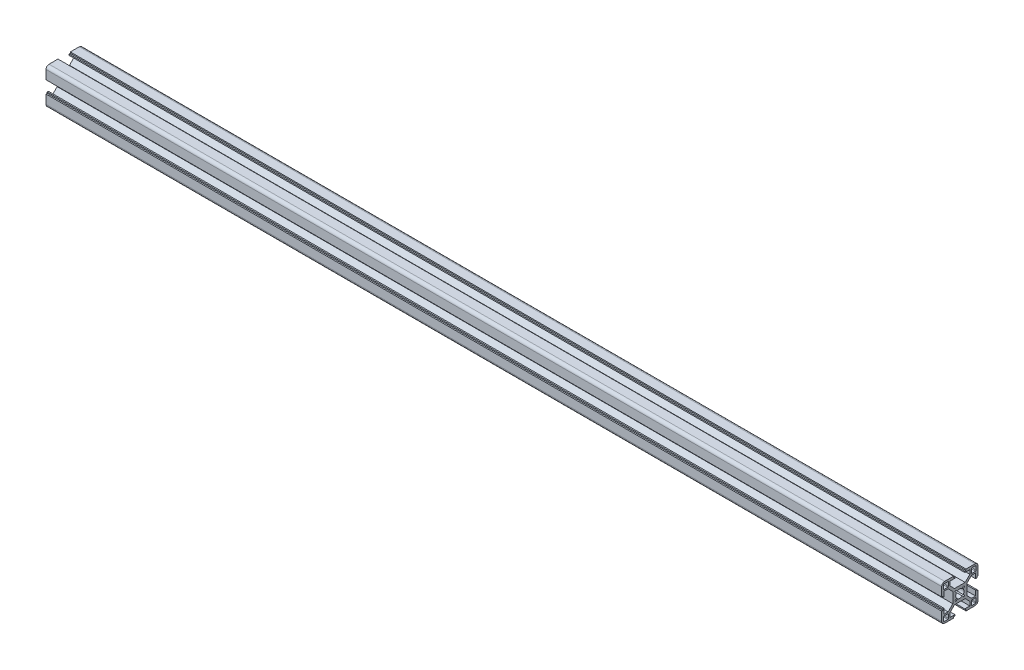
SolidWorks part; units mm, degrees
ref_plane "前视基准面" through (0, 0, 0) normal (0, 0, 1) x (1, 0, 0)
ref_plane "上视基准面" through (0, 0, 0) normal (0, 1, 0) x (1, 0, 0)
ref_plane "右视基准面" through (0, 0, 0) normal (1, 0, 0) x (0, 0, -1)
other "Configuration Table"
sketch "草图1" plane through (0, 0, 0) normal (1, 0, 0) x (0, 0, -1)
  line L0 (-5.1496, -13.7047) -> (-4.1496, -13.7047)
  line L1 (-4.1496, -13.7047) -> (-4.1496, -12.7047)
  line L2 (-4.1496, -12.7047) -> (-8.2996, -12.7047)
  line L3 (-8.2996, -12.7047) -> (-8.2996, -9.3689)
  line L4 (-8.2996, -9.3689) -> (-4.4354, -5.5047)
  line L5 (-4.4354, -5.5047) -> (4.3362, -5.5047)
  line L6 (4.3362, -5.5047) -> (8.2004, -9.3689)
  line L7 (8.2004, -9.3689) -> (8.2004, -12.7047)
  line L8 (8.2004, -12.7047) -> (4.0504, -12.7047)
  line L9 (4.0504, -12.7047) -> (4.0504, -13.7047)
  line L10 (4.0504, -13.7047) -> (5.0504, -13.7047)
  line L11 (5.0504, -13.7047) -> (5.0504, -14.7047)
  line L12 (5.0504, -14.7047) -> (12.4504, -14.7047)
  line L13 (14.9504, -12.2047) -> (14.9504, -4.8047)
  line L14 (14.9504, -4.8047) -> (13.9504, -4.8047)
  line L15 (13.9504, -4.8047) -> (13.9504, -3.8047)
  line L16 (13.9504, -3.8047) -> (12.9504, -3.8047)
  line L17 (12.9504, -3.8047) -> (12.9504, -7.9547)
  line L18 (12.9504, -7.9547) -> (9.6146, -7.9547)
  line L19 (9.6146, -7.9547) -> (5.7504, -4.0905)
  line L20 (5.7504, -4.0905) -> (5.7504, 4.6811)
  line L21 (5.7504, 4.6811) -> (9.6146, 8.5453)
  line L22 (9.6146, 8.5453) -> (12.9504, 8.5453)
  line L23 (12.9504, 8.5453) -> (12.9504, 4.3953)
  line L24 (12.9504, 4.3953) -> (13.9504, 4.3953)
  line L25 (13.9504, 4.3953) -> (13.9504, 5.3953)
  line L26 (13.9504, 5.3953) -> (14.9504, 5.3953)
  line L27 (14.9504, 5.3953) -> (14.9504, 12.7953)
  line L28 (12.4504, 15.2953) -> (5.0504, 15.2953)
  line L29 (5.0504, 15.2953) -> (5.0504, 14.2953)
  line L30 (5.0504, 14.2953) -> (4.0504, 14.2953)
  line L31 (4.0504, 14.2953) -> (4.0504, 13.2953)
  line L32 (4.0504, 13.2953) -> (8.2004, 13.2953)
  line L33 (8.2004, 13.2953) -> (8.2004, 9.9595)
  line L34 (8.2004, 9.9595) -> (4.3362, 6.0953)
  line L35 (4.3362, 6.0953) -> (-4.4354, 6.0953)
  line L36 (-4.4354, 6.0953) -> (-8.2996, 9.9595)
  line L37 (-8.2996, 9.9595) -> (-8.2996, 13.2953)
  line L38 (-8.2996, 13.2953) -> (-4.1496, 13.2953)
  line L39 (-4.1496, 13.2953) -> (-4.1496, 14.2953)
  line L40 (-4.1496, 14.2953) -> (-5.1496, 14.2953)
  line L41 (-5.1496, 14.2953) -> (-5.1496, 15.2953)
  line L42 (-5.1496, 15.2953) -> (-12.5496, 15.2953)
  line L43 (-15.0496, 12.7953) -> (-15.0496, 5.3953)
  line L44 (-15.0496, 5.3953) -> (-14.0496, 5.3953)
  line L45 (-14.0496, 5.3953) -> (-14.0496, 4.3953)
  line L46 (-14.0496, 4.3953) -> (-13.0496, 4.3953)
  line L47 (-13.0496, 4.3953) -> (-13.0496, 8.5453)
  line L48 (-13.0496, 8.5453) -> (-9.7138, 8.5453)
  line L49 (-9.7138, 8.5453) -> (-5.8496, 4.6811)
  line L50 (-5.8496, 4.6811) -> (-5.8496, -4.0905)
  line L51 (-5.8496, -4.0905) -> (-9.7138, -7.9547)
  line L52 (-9.7138, -7.9547) -> (-13.0496, -7.9547)
  line L53 (-13.0496, -7.9547) -> (-13.0496, -3.8047)
  line L54 (-13.0496, -3.8047) -> (-14.0496, -3.8047)
  line L55 (-14.0496, -3.8047) -> (-14.0496, -4.8047)
  line L56 (-14.0496, -4.8047) -> (-15.0496, -4.8047)
  line L57 (-15.0496, -4.8047) -> (-15.0496, -12.2047)
  line L58 (-12.5496, -14.7047) -> (-5.1496, -14.7047)
  line L59 (-5.1496, -14.7047) -> (-5.1496, -13.7047)
  line L60 (-10.0496, 9.7953) -> (-13.0496, 9.7953)
  line L61 (-13.5496, 10.2953) -> (-13.5496, 13.2953)
  line L62 (-13.0496, 13.7953) -> (-10.0496, 13.7953)
  line L63 (-9.5496, 13.2953) -> (-9.5496, 10.2953)
  line L64 (-10.0496, -13.2047) -> (-13.0496, -13.2047)
  line L65 (-13.5496, -12.7047) -> (-13.5496, -9.7047)
  line L66 (-13.0496, -9.2047) -> (-10.0496, -9.2047)
  line L67 (-9.5496, -9.7047) -> (-9.5496, -12.7047)
  line L68 (12.9504, 9.7953) -> (9.9504, 9.7953)
  line L69 (9.4504, 10.2953) -> (9.4504, 13.2953)
  line L70 (9.9504, 13.7953) -> (12.9504, 13.7953)
  line L71 (13.4504, 13.2953) -> (13.4504, 10.2953)
  line L72 (13.4504, -9.7047) -> (13.4504, -12.7047)
  line L73 (12.9504, -13.2047) -> (9.9504, -13.2047)
  line L74 (9.4504, -12.7047) -> (9.4504, -9.7047)
  line L75 (9.9504, -9.2047) -> (12.9504, -9.2047)
  line L76 (-4.08, 3.6186) -> (-3.3729, 4.3257)
  line L77 (-3.3729, 4.3257) -> (-2.074, 3.0269)
  line L78 (1.9749, 3.0269) -> (3.2737, 4.3257)
  line L79 (3.2737, 4.3257) -> (3.9808, 3.6186)
  line L80 (3.9808, 3.6186) -> (2.682, 2.3198)
  line L81 (2.682, -1.7291) -> (3.9808, -3.028)
  line L82 (3.9808, -3.028) -> (3.2737, -3.7351)
  line L83 (3.2737, -3.7351) -> (1.9749, -2.4362)
  line L84 (-2.074, -2.4362) -> (-3.3729, -3.7351)
  line L85 (-3.3729, -3.7351) -> (-4.08, -3.028)
  line L86 (-4.08, -3.028) -> (-2.7811, -1.7291)
  line L87 (-2.7811, 2.3198) -> (-4.08, 3.6186)
  arc A0 (12.4504, -14.7047) -> (14.9504, -12.2047) centre (12.4504, -12.2047) ccw
  arc A1 (14.9504, 12.7953) -> (12.4504, 15.2953) centre (12.4504, 12.7953) ccw
  arc A2 (-12.5496, 15.2953) -> (-15.0496, 12.7953) centre (-12.5496, 12.7953) ccw
  arc A3 (-15.0496, -12.2047) -> (-12.5496, -14.7047) centre (-12.5496, -12.2047) ccw
  arc A4 (-9.5496, 10.2953) -> (-10.0496, 9.7953) centre (-10.0496, 10.2953) cw
  arc A5 (-13.0496, 9.7953) -> (-13.5496, 10.2953) centre (-13.0496, 10.2953) cw
  arc A6 (-13.5496, 13.2953) -> (-13.0496, 13.7953) centre (-13.0496, 13.2953) cw
  arc A7 (-10.0496, 13.7953) -> (-9.5496, 13.2953) centre (-10.0496, 13.2953) cw
  arc A8 (-9.5496, -12.7047) -> (-10.0496, -13.2047) centre (-10.0496, -12.7047) cw
  arc A9 (-13.0496, -13.2047) -> (-13.5496, -12.7047) centre (-13.0496, -12.7047) cw
  arc A10 (-13.5496, -9.7047) -> (-13.0496, -9.2047) centre (-13.0496, -9.7047) cw
  arc A11 (-10.0496, -9.2047) -> (-9.5496, -9.7047) centre (-10.0496, -9.7047) cw
  arc A12 (13.4504, 10.2953) -> (12.9504, 9.7953) centre (12.9504, 10.2953) cw
  arc A13 (9.9504, 9.7953) -> (9.4504, 10.2953) centre (9.9504, 10.2953) cw
  arc A14 (9.4504, 13.2953) -> (9.9504, 13.7953) centre (9.9504, 13.2953) cw
  arc A15 (12.9504, 13.7953) -> (13.4504, 13.2953) centre (12.9504, 13.2953) cw
  arc A16 (12.9504, -9.2047) -> (13.4504, -9.7047) centre (12.9504, -9.7047) cw
  arc A17 (13.4504, -12.7047) -> (12.9504, -13.2047) centre (12.9504, -12.7047) cw
  arc A18 (9.9504, -13.2047) -> (9.4504, -12.7047) centre (9.9504, -12.7047) cw
  arc A19 (9.4504, -9.7047) -> (9.9504, -9.2047) centre (9.9504, -9.7047) cw
  arc A20 (-2.074, 3.0269) -> (1.9749, 3.0269) centre (-0.0496, 0.2953) cw
  arc A21 (2.682, 2.3198) -> (2.682, -1.7291) centre (-0.0496, 0.2953) cw
  arc A22 (1.9749, -2.4362) -> (-2.074, -2.4362) centre (-0.0496, 0.2953) cw
  arc A23 (-2.7811, -1.7291) -> (-2.7811, 2.3198) centre (-0.0496, 0.2953) cw
extrude "凸台-拉伸1" add sketch "草图1" against normal blind 50
sketch "草图2" plane through (0, 0, 0) normal (1, 0, 0) x (0, 0, -1)
  line L4 (-13.0496, 9.7953) -> (-10.0496, 9.7953)
  line L5 (-13.5496, 13.2953) -> (-13.5496, 10.2953)
  line L6 (-10.0496, 13.7953) -> (-13.0496, 13.7953)
  line L7 (-9.5496, 10.2953) -> (-9.5496, 13.2953)
  line L8 (-13.0496, 9.7953) -> (-10.0496, 9.7953)
  line L9 (-13.5496, 13.2953) -> (-13.5496, 10.2953)
  line L10 (-10.0496, 13.7953) -> (-13.0496, 13.7953)
  line L11 (-9.5496, 10.2953) -> (-9.5496, 13.2953)
  line L12 (-13.0496, -13.2047) -> (-10.0496, -13.2047)
  line L13 (-13.5496, -9.7047) -> (-13.5496, -12.7047)
  line L14 (-10.0496, -9.2047) -> (-13.0496, -9.2047)
  line L15 (-9.5496, -12.7047) -> (-9.5496, -9.7047)
  line L16 (-13.0496, -13.2047) -> (-10.0496, -13.2047)
  line L17 (-13.5496, -9.7047) -> (-13.5496, -12.7047)
  line L18 (-10.0496, -9.2047) -> (-13.0496, -9.2047)
  line L19 (-9.5496, -12.7047) -> (-9.5496, -9.7047)
  line L20 (9.4504, 13.2953) -> (9.4504, 10.2953)
  line L21 (12.9504, 13.7953) -> (9.9504, 13.7953)
  line L22 (13.4504, 10.2953) -> (13.4504, 13.2953)
  line L23 (9.9504, 9.7953) -> (12.9504, 9.7953)
  line L24 (9.4504, 13.2953) -> (9.4504, 10.2953)
  line L25 (12.9504, 13.7953) -> (9.9504, 13.7953)
  line L26 (13.4504, 10.2953) -> (13.4504, 13.2953)
  line L27 (9.9504, 9.7953) -> (12.9504, 9.7953)
  line L28 (9.4504, -9.7047) -> (9.4504, -12.7047)
  line L29 (12.9504, -9.2047) -> (9.9504, -9.2047)
  line L30 (13.4504, -12.7047) -> (13.4504, -9.7047)
  line L31 (9.9504, -13.2047) -> (12.9504, -13.2047)
  line L32 (9.4504, -9.7047) -> (9.4504, -12.7047)
  line L33 (12.9504, -9.2047) -> (9.9504, -9.2047)
  line L34 (13.4504, -12.7047) -> (13.4504, -9.7047)
  line L35 (9.9504, -13.2047) -> (12.9504, -13.2047)
  line L44 (-3.3729, -3.7351) -> (-2.074, -2.4362)
  line L45 (-4.08, -3.028) -> (-3.3729, -3.7351)
  line L46 (-2.7811, -1.7291) -> (-4.08, -3.028)
  line L47 (-4.08, 3.6186) -> (-2.7811, 2.3198)
  line L48 (-3.3729, 4.3257) -> (-4.08, 3.6186)
  line L49 (-2.074, 3.0269) -> (-3.3729, 4.3257)
  line L50 (3.2737, 4.3257) -> (1.9749, 3.0269)
  line L51 (3.9808, 3.6186) -> (3.2737, 4.3257)
  line L52 (2.682, 2.3198) -> (3.9808, 3.6186)
  line L53 (3.9808, -3.028) -> (2.682, -1.7291)
  line L54 (3.2737, -3.7351) -> (3.9808, -3.028)
  line L55 (1.9749, -2.4362) -> (3.2737, -3.7351)
  line L56 (-3.3729, -3.7351) -> (-2.074, -2.4362)
  line L57 (-4.08, -3.028) -> (-3.3729, -3.7351)
  line L58 (-2.7811, -1.7291) -> (-4.08, -3.028)
  line L59 (-4.08, 3.6186) -> (-2.7811, 2.3198)
  line L60 (-3.3729, 4.3257) -> (-4.08, 3.6186)
  line L61 (-2.074, 3.0269) -> (-3.3729, 4.3257)
  line L62 (3.2737, 4.3257) -> (1.9749, 3.0269)
  line L63 (3.9808, 3.6186) -> (3.2737, 4.3257)
  line L64 (2.682, 2.3198) -> (3.9808, 3.6186)
  line L65 (3.9808, -3.028) -> (2.682, -1.7291)
  line L66 (3.2737, -3.7351) -> (3.9808, -3.028)
  line L67 (1.9749, -2.4362) -> (3.2737, -3.7351)
  line L68 (-15.0496, -4.8047) -> (-15.0496, -12.2047)
  line L69 (-14.0496, -4.8047) -> (-15.0496, -4.8047)
  line L70 (-14.0496, -3.8047) -> (-14.0496, -4.8047)
  line L71 (-13.0496, -3.8047) -> (-14.0496, -3.8047)
  line L72 (-13.0496, -7.9547) -> (-13.0496, -3.8047)
  line L73 (-9.7138, -7.9547) -> (-13.0496, -7.9547)
  line L74 (-5.8496, -4.0905) -> (-9.7138, -7.9547)
  line L75 (-5.8496, 4.6811) -> (-5.8496, -4.0905)
  line L76 (-9.7138, 8.5453) -> (-5.8496, 4.6811)
  line L77 (-13.0496, 8.5453) -> (-9.7138, 8.5453)
  line L78 (-13.0496, 4.3953) -> (-13.0496, 8.5453)
  line L79 (-14.0496, 4.3953) -> (-13.0496, 4.3953)
  line L80 (-14.0496, 5.3953) -> (-14.0496, 4.3953)
  line L81 (-15.0496, 5.3953) -> (-14.0496, 5.3953)
  line L82 (-15.0496, 12.7953) -> (-15.0496, 5.3953)
  line L83 (-5.1496, 15.2953) -> (-12.5496, 15.2953)
  line L84 (-5.1496, 14.2953) -> (-5.1496, 15.2953)
  line L85 (-4.1496, 14.2953) -> (-5.1496, 14.2953)
  line L86 (-4.1496, 13.2953) -> (-4.1496, 14.2953)
  line L87 (-8.2996, 13.2953) -> (-4.1496, 13.2953)
  line L88 (-8.2996, 9.9595) -> (-8.2996, 13.2953)
  line L89 (-4.4354, 6.0953) -> (-8.2996, 9.9595)
  line L90 (4.3362, 6.0953) -> (-4.4354, 6.0953)
  line L91 (8.2004, 9.9595) -> (4.3362, 6.0953)
  line L92 (8.2004, 13.2953) -> (8.2004, 9.9595)
  line L93 (4.0504, 13.2953) -> (8.2004, 13.2953)
  line L94 (4.0504, 14.2953) -> (4.0504, 13.2953)
  line L95 (5.0504, 14.2953) -> (4.0504, 14.2953)
  line L96 (5.0504, 15.2953) -> (5.0504, 14.2953)
  line L97 (12.4504, 15.2953) -> (5.0504, 15.2953)
  line L98 (14.9504, 5.3953) -> (14.9504, 12.7953)
  line L99 (13.9504, 5.3953) -> (14.9504, 5.3953)
  line L100 (13.9504, 4.3953) -> (13.9504, 5.3953)
  line L101 (12.9504, 4.3953) -> (13.9504, 4.3953)
  line L102 (12.9504, 8.5453) -> (12.9504, 4.3953)
  line L103 (9.6146, 8.5453) -> (12.9504, 8.5453)
  line L104 (5.7504, 4.6811) -> (9.6146, 8.5453)
  line L105 (5.7504, -4.0905) -> (5.7504, 4.6811)
  line L106 (9.6146, -7.9547) -> (5.7504, -4.0905)
  line L107 (12.9504, -7.9547) -> (9.6146, -7.9547)
  line L108 (12.9504, -3.8047) -> (12.9504, -7.9547)
  line L109 (13.9504, -3.8047) -> (12.9504, -3.8047)
  line L110 (13.9504, -4.8047) -> (13.9504, -3.8047)
  line L111 (14.9504, -4.8047) -> (13.9504, -4.8047)
  line L112 (14.9504, -12.2047) -> (14.9504, -4.8047)
  line L113 (5.0504, -14.7047) -> (12.4504, -14.7047)
  line L114 (5.0504, -13.7047) -> (5.0504, -14.7047)
  line L115 (4.0504, -13.7047) -> (5.0504, -13.7047)
  line L116 (4.0504, -12.7047) -> (4.0504, -13.7047)
  line L117 (8.2004, -12.7047) -> (4.0504, -12.7047)
  line L118 (8.2004, -9.3689) -> (8.2004, -12.7047)
  line L119 (4.3362, -5.5047) -> (8.2004, -9.3689)
  line L120 (-4.4354, -5.5047) -> (4.3362, -5.5047)
  line L121 (-8.2996, -9.3689) -> (-4.4354, -5.5047)
  line L122 (-8.2996, -12.7047) -> (-8.2996, -9.3689)
  line L123 (-4.1496, -12.7047) -> (-8.2996, -12.7047)
  line L124 (-4.1496, -13.7047) -> (-4.1496, -12.7047)
  line L125 (-5.1496, -13.7047) -> (-4.1496, -13.7047)
  line L126 (-5.1496, -14.7047) -> (-5.1496, -13.7047)
  line L127 (-12.5496, -14.7047) -> (-5.1496, -14.7047)
  line L128 (-15.0496, -4.8047) -> (-15.0496, -12.2047)
  line L129 (-14.0496, -4.8047) -> (-15.0496, -4.8047)
  line L130 (-14.0496, -3.8047) -> (-14.0496, -4.8047)
  line L131 (-13.0496, -3.8047) -> (-14.0496, -3.8047)
  line L132 (-13.0496, -7.9547) -> (-13.0496, -3.8047)
  line L133 (-9.7138, -7.9547) -> (-13.0496, -7.9547)
  line L134 (-5.8496, -4.0905) -> (-9.7138, -7.9547)
  line L135 (-5.8496, 4.6811) -> (-5.8496, -4.0905)
  line L136 (-9.7138, 8.5453) -> (-5.8496, 4.6811)
  line L137 (-13.0496, 8.5453) -> (-9.7138, 8.5453)
  line L138 (-13.0496, 4.3953) -> (-13.0496, 8.5453)
  line L139 (-14.0496, 4.3953) -> (-13.0496, 4.3953)
  line L140 (-14.0496, 5.3953) -> (-14.0496, 4.3953)
  line L141 (-15.0496, 5.3953) -> (-14.0496, 5.3953)
  line L142 (-15.0496, 12.7953) -> (-15.0496, 5.3953)
  line L143 (-5.1496, 15.2953) -> (-12.5496, 15.2953)
  line L144 (-5.1496, 14.2953) -> (-5.1496, 15.2953)
  line L145 (-4.1496, 14.2953) -> (-5.1496, 14.2953)
  line L146 (-4.1496, 13.2953) -> (-4.1496, 14.2953)
  line L147 (-8.2996, 13.2953) -> (-4.1496, 13.2953)
  line L148 (-8.2996, 9.9595) -> (-8.2996, 13.2953)
  line L149 (-4.4354, 6.0953) -> (-8.2996, 9.9595)
  line L150 (4.3362, 6.0953) -> (-4.4354, 6.0953)
  line L151 (8.2004, 9.9595) -> (4.3362, 6.0953)
  line L152 (8.2004, 13.2953) -> (8.2004, 9.9595)
  line L153 (4.0504, 13.2953) -> (8.2004, 13.2953)
  line L154 (4.0504, 14.2953) -> (4.0504, 13.2953)
  line L155 (5.0504, 14.2953) -> (4.0504, 14.2953)
  line L156 (5.0504, 15.2953) -> (5.0504, 14.2953)
  line L157 (12.4504, 15.2953) -> (5.0504, 15.2953)
  line L158 (14.9504, 5.3953) -> (14.9504, 12.7953)
  line L159 (13.9504, 5.3953) -> (14.9504, 5.3953)
  line L160 (13.9504, 4.3953) -> (13.9504, 5.3953)
  line L161 (12.9504, 4.3953) -> (13.9504, 4.3953)
  line L162 (12.9504, 8.5453) -> (12.9504, 4.3953)
  line L163 (9.6146, 8.5453) -> (12.9504, 8.5453)
  line L164 (5.7504, 4.6811) -> (9.6146, 8.5453)
  line L165 (5.7504, -4.0905) -> (5.7504, 4.6811)
  line L166 (9.6146, -7.9547) -> (5.7504, -4.0905)
  line L167 (12.9504, -7.9547) -> (9.6146, -7.9547)
  line L168 (12.9504, -3.8047) -> (12.9504, -7.9547)
  line L169 (13.9504, -3.8047) -> (12.9504, -3.8047)
  line L170 (13.9504, -4.8047) -> (13.9504, -3.8047)
  line L171 (14.9504, -4.8047) -> (13.9504, -4.8047)
  line L172 (14.9504, -12.2047) -> (14.9504, -4.8047)
  line L173 (5.0504, -14.7047) -> (12.4504, -14.7047)
  line L174 (5.0504, -13.7047) -> (5.0504, -14.7047)
  line L175 (4.0504, -13.7047) -> (5.0504, -13.7047)
  line L176 (4.0504, -12.7047) -> (4.0504, -13.7047)
  line L177 (8.2004, -12.7047) -> (4.0504, -12.7047)
  line L178 (8.2004, -9.3689) -> (8.2004, -12.7047)
  line L179 (4.3362, -5.5047) -> (8.2004, -9.3689)
  line L180 (-4.4354, -5.5047) -> (4.3362, -5.5047)
  line L181 (-8.2996, -9.3689) -> (-4.4354, -5.5047)
  line L182 (-8.2996, -12.7047) -> (-8.2996, -9.3689)
  line L183 (-4.1496, -12.7047) -> (-8.2996, -12.7047)
  line L184 (-4.1496, -13.7047) -> (-4.1496, -12.7047)
  line L185 (-5.1496, -13.7047) -> (-4.1496, -13.7047)
  line L186 (-5.1496, -14.7047) -> (-5.1496, -13.7047)
  line L187 (-12.5496, -14.7047) -> (-5.1496, -14.7047)
  arc A4 (-13.5496, 10.2953) -> (-13.0496, 9.7953) centre (-13.0496, 10.2953) ccw
  arc A5 (-13.0496, 13.7953) -> (-13.5496, 13.2953) centre (-13.0496, 13.2953) ccw
  arc A6 (-9.5496, 13.2953) -> (-10.0496, 13.7953) centre (-10.0496, 13.2953) ccw
  arc A7 (-10.0496, 9.7953) -> (-9.5496, 10.2953) centre (-10.0496, 10.2953) ccw
  arc A8 (-13.5496, 10.2953) -> (-13.0496, 9.7953) centre (-13.0496, 10.2953) ccw
  arc A9 (-13.0496, 13.7953) -> (-13.5496, 13.2953) centre (-13.0496, 13.2953) ccw
  arc A10 (-9.5496, 13.2953) -> (-10.0496, 13.7953) centre (-10.0496, 13.2953) ccw
  arc A11 (-10.0496, 9.7953) -> (-9.5496, 10.2953) centre (-10.0496, 10.2953) ccw
  arc A12 (-12.5496, 15.2953) -> (-15.0496, 12.7953) centre (-12.5496, 12.7953) ccw
  arc A13 (14.9504, 12.7953) -> (12.4504, 15.2953) centre (12.4504, 12.7953) ccw
  arc A14 (12.4504, -14.7047) -> (14.9504, -12.2047) centre (12.4504, -12.2047) ccw
  arc A15 (-15.0496, -12.2047) -> (-12.5496, -14.7047) centre (-12.5496, -12.2047) ccw
  arc A16 (-12.5496, 15.2953) -> (-15.0496, 12.7953) centre (-12.5496, 12.7953) ccw
  arc A17 (14.9504, 12.7953) -> (12.4504, 15.2953) centre (12.4504, 12.7953) ccw
  arc A18 (12.4504, -14.7047) -> (14.9504, -12.2047) centre (12.4504, -12.2047) ccw
  arc A19 (-15.0496, -12.2047) -> (-12.5496, -14.7047) centre (-12.5496, -12.2047) ccw
  arc A20 (-13.5496, -12.7047) -> (-13.0496, -13.2047) centre (-13.0496, -12.7047) ccw
  arc A21 (-13.0496, -9.2047) -> (-13.5496, -9.7047) centre (-13.0496, -9.7047) ccw
  arc A22 (-9.5496, -9.7047) -> (-10.0496, -9.2047) centre (-10.0496, -9.7047) ccw
  arc A23 (-10.0496, -13.2047) -> (-9.5496, -12.7047) centre (-10.0496, -12.7047) ccw
  arc A24 (-13.5496, -12.7047) -> (-13.0496, -13.2047) centre (-13.0496, -12.7047) ccw
  arc A25 (-13.0496, -9.2047) -> (-13.5496, -9.7047) centre (-13.0496, -9.7047) ccw
  arc A26 (-9.5496, -9.7047) -> (-10.0496, -9.2047) centre (-10.0496, -9.7047) ccw
  arc A27 (-10.0496, -13.2047) -> (-9.5496, -12.7047) centre (-10.0496, -12.7047) ccw
  arc A28 (9.9504, 13.7953) -> (9.4504, 13.2953) centre (9.9504, 13.2953) ccw
  arc A29 (13.4504, 13.2953) -> (12.9504, 13.7953) centre (12.9504, 13.2953) ccw
  arc A30 (12.9504, 9.7953) -> (13.4504, 10.2953) centre (12.9504, 10.2953) ccw
  arc A31 (9.4504, 10.2953) -> (9.9504, 9.7953) centre (9.9504, 10.2953) ccw
  arc A32 (9.9504, 13.7953) -> (9.4504, 13.2953) centre (9.9504, 13.2953) ccw
  arc A33 (13.4504, 13.2953) -> (12.9504, 13.7953) centre (12.9504, 13.2953) ccw
  arc A34 (12.9504, 9.7953) -> (13.4504, 10.2953) centre (12.9504, 10.2953) ccw
  arc A35 (9.4504, 10.2953) -> (9.9504, 9.7953) centre (9.9504, 10.2953) ccw
  arc A36 (9.9504, -9.2047) -> (9.4504, -9.7047) centre (9.9504, -9.7047) ccw
  arc A37 (13.4504, -9.7047) -> (12.9504, -9.2047) centre (12.9504, -9.7047) ccw
  arc A38 (12.9504, -13.2047) -> (13.4504, -12.7047) centre (12.9504, -12.7047) ccw
  arc A39 (9.4504, -12.7047) -> (9.9504, -13.2047) centre (9.9504, -12.7047) ccw
  arc A40 (9.9504, -9.2047) -> (9.4504, -9.7047) centre (9.9504, -9.7047) ccw
  arc A41 (13.4504, -9.7047) -> (12.9504, -9.2047) centre (12.9504, -9.7047) ccw
  arc A42 (12.9504, -13.2047) -> (13.4504, -12.7047) centre (12.9504, -12.7047) ccw
  arc A43 (9.4504, -12.7047) -> (9.9504, -13.2047) centre (9.9504, -12.7047) ccw
  arc A44 (-2.7811, 2.3198) -> (-2.7811, -1.7291) centre (-0.0496, 0.2953) ccw
  arc A45 (1.9749, 3.0269) -> (-2.074, 3.0269) centre (-0.0496, 0.2953) ccw
  arc A46 (2.682, -1.7291) -> (2.682, 2.3198) centre (-0.0496, 0.2953) ccw
  arc A47 (-2.074, -2.4362) -> (1.9749, -2.4362) centre (-0.0496, 0.2953) ccw
  arc A48 (-2.7811, 2.3198) -> (-2.7811, -1.7291) centre (-0.0496, 0.2953) ccw
  arc A49 (1.9749, 3.0269) -> (-2.074, 3.0269) centre (-0.0496, 0.2953) ccw
  arc A50 (2.682, -1.7291) -> (2.682, 2.3198) centre (-0.0496, 0.2953) ccw
  arc A51 (-2.074, -2.4362) -> (1.9749, -2.4362) centre (-0.0496, 0.2953) ccw
  dimension "D1" = 0
  dimension "D2" = 0
  dimension "D3" = 0
  dimension "D4" = 0
  dimension "D5" = 0
  dimension "D6" = 0
extrude "凸台-拉伸2" add sketch "草图2" against normal blind 740
sketch "草图4" plane through (0, 0, 0) normal (0, 0, 1) x (1, 0, 0)
  line L0 (-1000, 0) -> (49000, 0) construction
  line L1 (-370, -1000) -> (-370, 49000) construction
  line L2 (-740, 4.6811) -> (-740, -4.0905) construction
  circle A0 centre (-726.5, 0) radius 3
  circle A1 centre (-13.5, 0) radius 3
  dimension "D2" = 6
  dimension "D1" = 370
  dimension "D3" = 13.5
extrude "切除-拉伸1" cut sketch "草图4" against normal up to surface (30 mm away) from surface at 15.0496 up to face at (-370, -8.5047, -14.9504) starting at face at (-370, -8.5047, 15.0496)
sketch "草图5" plane through (0, 0, 0) normal (0, 1, 0) x (1, 0, 0)
  line L0 (-1000, 0) -> (49000, 0) construction
  line L1 (-370, -1000) -> (-370, 49000) construction
  line L2 (-407.5, 0) -> (-332.5, 0) construction
  circle A0 centre (-407.5, 0) radius 3
  circle A1 centre (-332.5, 0) radius 3
  point P8 (-370, 0)
  dimension "D3" = 6
  dimension "D4" = 6
  dimension "D1" = 370
  dimension "D2" = 75
extrude "切除-拉伸2" cut sketch "草图5" against normal up to surface (30 mm away) from surface at 15.2953 up to face at (-370, -14.7047, 8.8496) starting at face at (-370, 15.2953, 8.8496)
